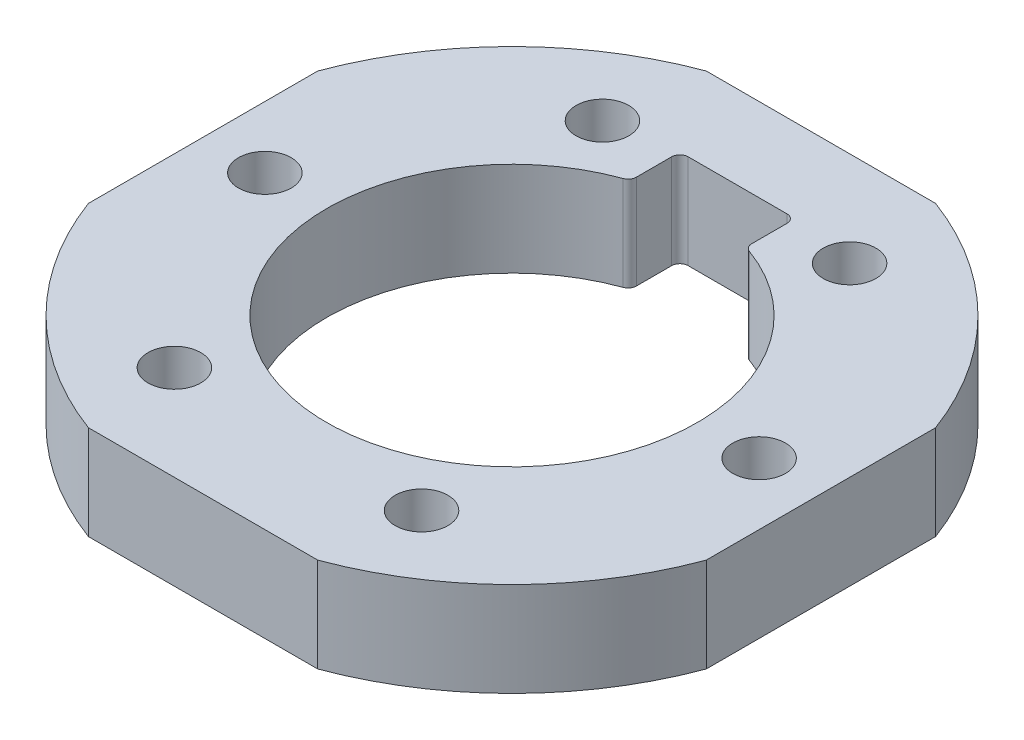
SolidWorks part; units mm, degrees
material "6061 Alloy"
ref_plane "Front Plane" through (0, 0, 0) normal (0, 0, 1) x (1, 0, 0)
ref_plane "Top Plane" through (0, 0, 0) normal (0, 1, 0) x (1, 0, 0)
ref_plane "Right Plane" through (0, 0, 0) normal (1, 0, 0) x (0, 0, -1)
sketch "Sketch1" plane through (0, 0, 0) normal (0, 1, 0) x (1, 0, 0)
  line L0 (-7.5664, 10.2) -> (7.5664, 10.2) construction
  line L1 (-7.5664, -10.2) -> (7.5664, -10.2) construction
  line L2 (-7, 21.3834) -> (-7, 27.3834)
  line L3 (-7, 27.3834) -> (7, 27.3834)
  line L4 (7, 27.3834) -> (7, 21.3834)
  line L5 (-13.9194, 37.5) -> (13.9194, 37.5)
  line L6 (-37.5, 13.9194) -> (-37.5, -13.9194)
  line L7 (-13.9194, -37.5) -> (13.9194, -37.5)
  line L8 (37.5, 13.9194) -> (37.5, -13.9194)
  arc A0 (-7.5664, 10.2) -> (-7.5664, -10.2) centre (0, 0) ccw construction
  arc A1 (7.5664, -10.2) -> (7.5664, 10.2) centre (0, 0) ccw construction
  circle A2 centre (0, 0) radius 40
  circle A3 centre (0, 0) radius 30 construction
  circle A4 centre (-30, 0) radius 3 construction
  circle A5 centre (-15, 25.9808) radius 3 construction
  circle A6 centre (15, 25.9808) radius 3 construction
  circle A7 centre (30, 0) radius 3 construction
  circle A8 centre (15, -25.9808) radius 3 construction
  circle A9 centre (-15, -25.9808) radius 3 construction
  circle A10 centre (0, 0) radius 22.5
  point P19 (0, 0)
  point P38 (0, 0)
  dimension "D1" = 12.7
  dimension "D3" = 80
  dimension "D4" = 60
  dimension "D6" = 6
  dimension "D7" = 45
  dimension "D8" = 75
  dimension "D2" = 20.4
  dimension "D10" = 14
  dimension "D11" = 6
  dimension "D5" = 6
extrude "Boss-Extrude1" add sketch "Sketch1" against normal blind 11.45
hole_wizard "M6 Clearance Hole1" positions "3DSketch1" profile "Sketch2" hole size "M6" standard "ANSI Metric" end condition up to next
sketch3d "3DSketch1"
  point P0 (-30, 0, 0)
  point P2 (-15, 0, -25.9808)
  point P4 (15, 0, -25.9808)
  point P6 (30, 0, 0)
  point P8 (15, 0, 25.9808)
  point P10 (-15, 0, 25.9808)
sketch "Sketch2" plane through (-30, 0, 0) normal (1, 0, 0) x (0, 0, 1)
  line L0 (0, 0) -> (0, 11.45)
  line L1 (0, 11.45) -> (3.2, 11.45)
  line L2 (3.2, 11.45) -> (3.2, 0)
  line L5 (3.2, 0) -> (0, 0)
  line L11 (0, -6.35) -> (0, 107.95) construction
  dimension "Thru Hole Dia." = 6.4
  dimension "Thru Hole Depth" = 11.45
fillet "Fillet1" radius 1 4 edges at (7, -5.725, -27.3834) (-7, -5.725, -27.3834) (7, -5.725, -21.3834) (-7, -5.725, -21.3834)
